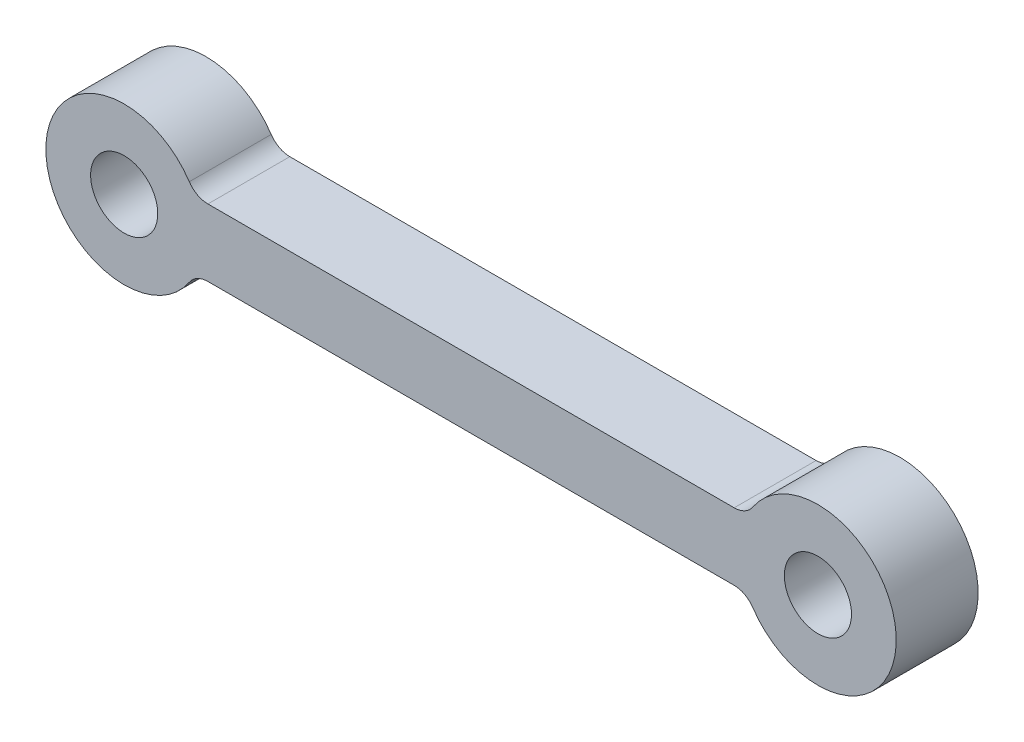
SolidWorks part; units mm, degrees
ref_plane "Front Plane" through (0, 0, 0) normal (0, 0, 1) x (1, 0, 0)
ref_plane "Top Plane" through (0, 0, 0) normal (0, 1, 0) x (1, 0, 0)
ref_plane "Right Plane" through (0, 0, 0) normal (1, 0, 0) x (0, 0, -1)
sketch "Sketch1" plane through (0, 0, 0) normal (0, 0, 1) x (1, 0, 0)
  line L0 (-15.5, 0) -> (15.5, 0) construction
  line L1 (-15.5, 3.5) -> (15.5, 3.5) construction
  line L2 (-15.5, -3.5) -> (15.5, -3.5) construction
  line L4 (-12.3377, 1.5) -> (12.3377, 1.5)
  line L6 (-12.3377, -1.5) -> (12.3377, -1.5)
  line L8 (-12.3377, 1.5) -> (12.3377, -1.5) construction
  line L9 (-12.3377, -1.5) -> (12.3377, 1.5) construction
  arc A0 (-15.5, 3.5) -> (-15.5, -3.5) centre (-15.5, 0) ccw construction
  arc A1 (15.5, -3.5) -> (15.5, 3.5) centre (15.5, 0) ccw construction
  circle A2 centre (-15.5, 0) radius 3.5
  circle A3 centre (15.5, 0) radius 3.5
  circle A4 centre (-15.5, 0) radius 1.5
  circle A5 centre (15.5, 0) radius 1.5
  point P3 (0, 0)
  point P14 (0, 0)
  dimension "D3" = 3
  dimension "D1" = 31
  dimension "D2" = 7
  dimension "D4" = 3
extrude "Boss-Extrude1" add sketch "Sketch1" along normal mid plane 3.66
fillet "Fillet1" radius 1 4 edges at (-12.3377, 1.5, 0) (12.3377, -1.5, 0) (-12.3377, -1.5, 0) (12.3377, 1.5, 0)
